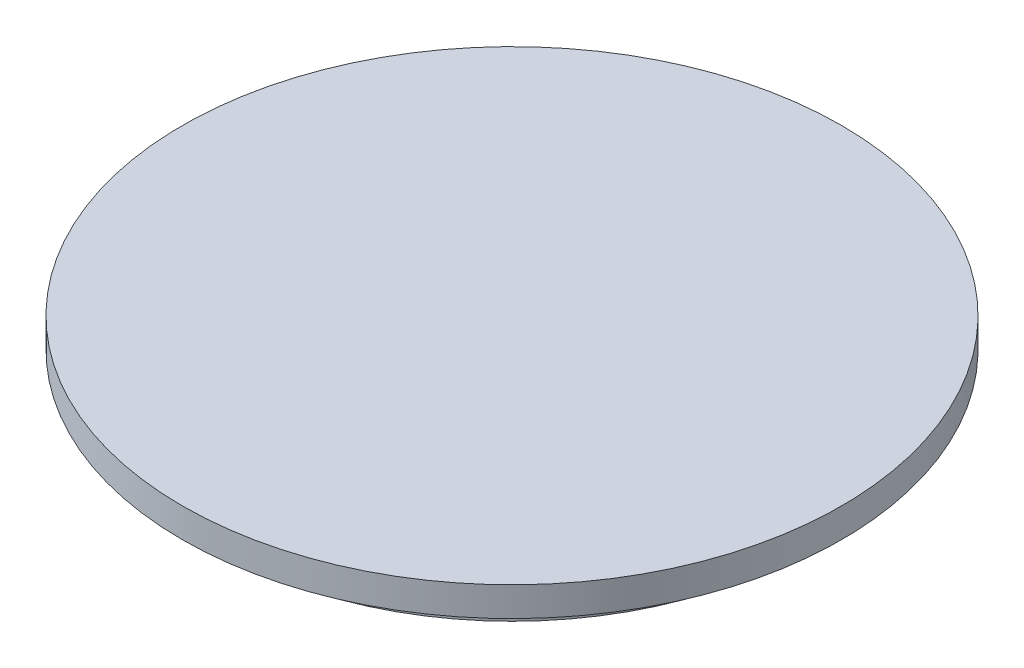
SolidWorks part; units mm, degrees
ref_plane "Ebene vorne" through (0, 0, 0) normal (0, 0, 1) x (1, 0, 0)
ref_plane "Ebene oben" through (0, 0, 0) normal (0, 1, 0) x (1, 0, 0)
ref_plane "Ebene rechts" through (0, 0, 0) normal (1, 0, 0) x (0, 0, -1)
sketch "Skizze1" plane through (0, 0, 0) normal (0, 1, 0) x (1, 0, 0)
  circle A1 centre (0, 0) radius 22.5
extrude "Aufsatz-Linear austragen1" add sketch "Skizze1" along normal blind 2 contours A1
sketch "Skizze2" plane through (0, 0, 0) normal (0, 1, 0) x (1, 0, 0)
  circle A0 centre (0, 0) radius 19.9
  circle A1 centre (0, 0) radius 17.9
  dimension "D1" = 39.8
  dimension "D2" = 35.8
extrude "Aufsatz-Linear austragen2" add sketch "Skizze2" against normal blind 2
